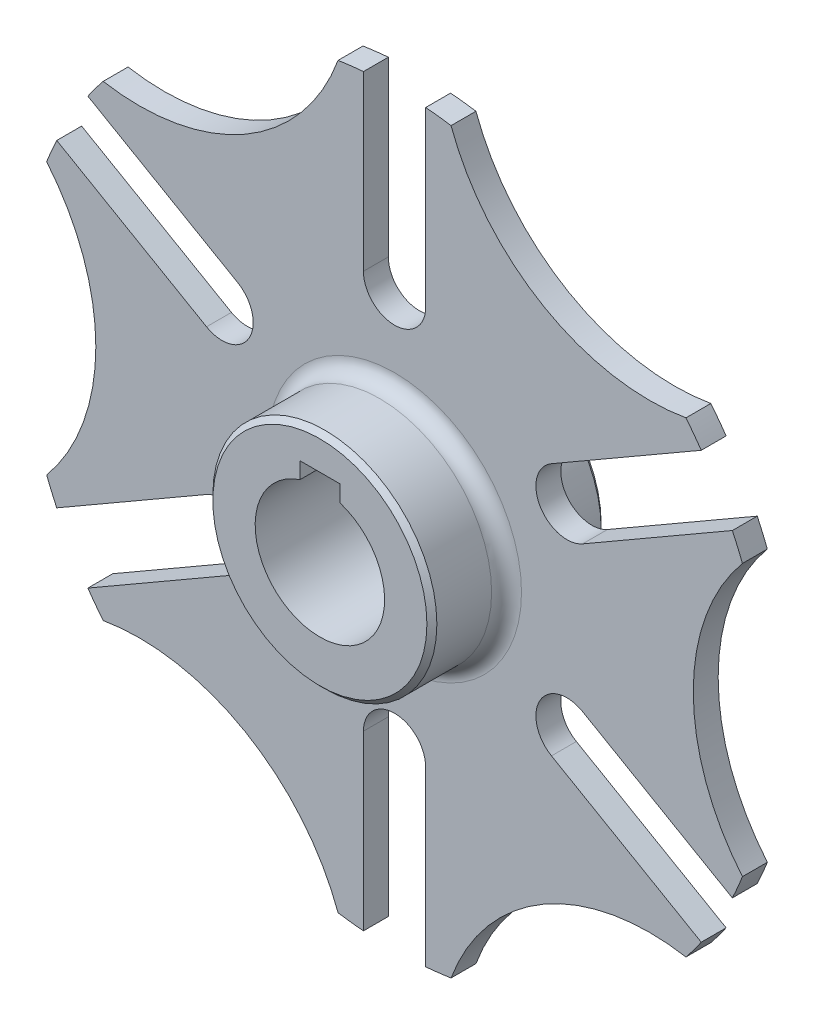
SolidWorks part; units mm, degrees
ref_plane "Front Plane" through (0, 0, 0) normal (0, 0, 1) x (1, 0, 0)
ref_plane "Top Plane" through (0, 0, 0) normal (0, 1, 0) x (1, 0, 0)
ref_plane "Right Plane" through (0, 0, 0) normal (1, 0, 0) x (0, 0, -1)
sketch "Sketch1" plane through (0, 0, 0) normal (0, 0, 1) x (1, 0, 0)
  circle A0 centre (0, 0) radius 75
  dimension "D1" = 150
extrude "Boss-Extrude1" add sketch "Sketch1" along normal mid plane 5 contours A0
sketch "Sketch2" plane through (0, 0, 0) normal (0, 0, 1) x (1, 0, 0)
  circle A0 centre (0, 0) radius 22.5
  dimension "D1" = 45
extrude "Boss-Extrude2" add sketch "Sketch2" along normal mid plane 35
sketch "Sketch3" plane through (0, 0, 17.5) normal (0, 0, 1) x (1, 0, 0)
  circle A0 centre (0, 0) radius 13
  dimension "D1" = 26
extrude "Cut-Extrude1" cut sketch "Sketch3" against normal blind 35
sketch "Sketch4" plane through (0, 0, 2.5) normal (0, 0, 1) x (1, 0, 0)
  line L0 (0, -90.256) -> (0, 75) construction
  line L1 (-102.8846, 0) -> (106.9882, 0) construction
  line L2 (0, 0) -> (62.7614, 108.7059) construction
  line L3 (0, 0) -> (51.25, 88.7676) construction
  line L4 (0, 40) -> (0, 75) construction
  line L5 (-6.25, 40) -> (-6.25, 74.7391)
  line L6 (6.25, 40) -> (6.25, 74.7391)
  line L7 (31.516, 25.4127) -> (61.601, 42.7822)
  line L8 (37.766, 14.5873) -> (67.851, 31.9569)
  line L9 (37.766, -14.5873) -> (67.851, -31.9569)
  line L10 (31.516, -25.4127) -> (61.601, -42.7822)
  line L11 (6.25, -40) -> (6.25, -74.7391)
  line L12 (-6.25, -40) -> (-6.25, -74.7391)
  line L13 (-31.516, -25.4127) -> (-61.601, -42.7822)
  line L14 (-37.766, -14.5873) -> (-67.851, -31.9569)
  line L15 (-37.766, 14.5873) -> (-67.851, 31.9569)
  line L16 (-31.516, 25.4127) -> (-61.601, 42.7822)
  circle A0 centre (0, 0) radius 102.5 construction
  arc A1 (11.3478, 74.1365) -> (58.5302, 46.8958) centre (51.25, 88.7676) ccw
  arc A2 (69.878, 27.2407) -> (69.878, -27.2407) centre (102.5, 0) ccw
  arc A3 (58.5302, -46.8958) -> (11.3478, -74.1365) centre (51.25, -88.7676) ccw
  arc A4 (-11.3478, -74.1365) -> (-58.5302, -46.8958) centre (-51.25, -88.7676) ccw
  arc A5 (-69.878, -27.2407) -> (-69.878, 27.2407) centre (-102.5, 0) ccw
  arc A6 (-58.5302, 46.8958) -> (-11.3478, 74.1365) centre (-51.25, 88.7676) ccw
  circle A7 centre (0, 0) radius 75 construction
  arc A8 (58.5302, 46.8958) -> (11.3478, 74.1365) centre (0, 0) ccw
  arc A9 (69.878, -27.2407) -> (69.878, 27.2407) centre (0, 0) ccw
  arc A10 (11.3478, -74.1365) -> (58.5302, -46.8958) centre (0, 0) ccw
  arc A11 (-58.5302, -46.8958) -> (-11.3478, -74.1365) centre (0, 0) ccw
  arc A12 (-69.878, 27.2407) -> (-69.878, -27.2407) centre (0, 0) ccw
  arc A13 (-11.3478, 74.1365) -> (-58.5302, 46.8958) centre (0, 0) ccw
  circle A14 centre (0, 0) radius 40 construction
  arc A15 (-6.25, 40) -> (6.25, 40) centre (0, 40) ccw
  arc A17 (-11.3478, 74.1365) -> (-58.5302, 46.8958) centre (0, 0) ccw
  arc A18 (6.25, 74.7391) -> (-6.25, 74.7391) centre (0, 0) ccw
  arc A19 (58.5302, 46.8958) -> (11.3478, 74.1365) centre (0, 0) ccw
  arc A20 (69.878, -27.2407) -> (69.878, 27.2407) centre (0, 0) ccw
  arc A21 (11.3478, -74.1365) -> (58.5302, -46.8958) centre (0, 0) ccw
  arc A22 (-58.5302, -46.8958) -> (-11.3478, -74.1365) centre (0, 0) ccw
  arc A23 (-69.878, 27.2407) -> (-69.878, -27.2407) centre (0, 0) ccw
  arc A24 (67.851, 31.9569) -> (61.601, 42.7822) centre (0, 0) ccw
  arc A25 (31.516, 25.4127) -> (37.766, 14.5873) centre (34.641, 20) ccw
  arc A26 (61.601, -42.7822) -> (67.851, -31.9569) centre (0, 0) ccw
  arc A27 (37.766, -14.5873) -> (31.516, -25.4127) centre (34.641, -20) ccw
  arc A28 (-6.25, -74.7391) -> (6.25, -74.7391) centre (0, 0) ccw
  arc A29 (6.25, -40) -> (-6.25, -40) centre (0, -40) ccw
  arc A30 (-67.851, -31.9569) -> (-61.601, -42.7822) centre (0, 0) ccw
  arc A31 (-31.516, -25.4127) -> (-37.766, -14.5873) centre (-34.641, -20) ccw
  arc A32 (-61.601, 42.7822) -> (-67.851, 31.9569) centre (0, 0) ccw
  arc A33 (-37.766, 14.5873) -> (-31.516, 25.4127) centre (-34.641, 20) ccw
  point P29 (0, 0)
  point P31 (0, 64.3838)
  point P63 (0, 0)
  circle M27 centre (0, 0) radius 75
  dimension "D2" = 205
  dimension "D3" = 42.5
  dimension "D4" = 6
  dimension "D5" = 80
  dimension "D1" = 30
  dimension "D6" = 12.5
  dimension "D7" = 6
extrude "Cut-Extrude2" cut sketch "Sketch4" against normal blind 35 contours A1 M27 | L7 A25 L8 M27 | A2 M27 | L9 A27 L10 M27 | A3 M27 | L11 A29 L12 M27 | A4 M27 | L13 A31 L14 M27 | A5 M27 | L15 A33 L16 M27 | A6 M27 | L5 A15 L6 M27
sketch "Sketch5" plane through (0, 0, 17.5) normal (0, 0, 1) x (1, 0, 0)
  line L0 (-4, 12.3693) -> (-4, 15.6693)
  line L3 (-4, 15.6693) -> (4, 15.6693)
  line L6 (-4, 15.6693) -> (-3.2155, 12.5961) construction
  line L8 (3.3163, 12.5699) -> (4, 15.6693) construction
  line L9 (4, 12.3693) -> (4, 15.6693)
  circle A0 centre (0, 0) radius 13 construction
  arc A1 (4, 12.3693) -> (-4, 12.3693) centre (0, 0) ccw
  point P0 (0, 0)
  dimension "D1" = 8
  dimension "D2" = 3.3
extrude "Cut-Extrude3" cut sketch "Sketch5" against normal blind 35
chamfer "Chamfer1" distance 1 angle 45 1 edges at (22.5, 0, 17.5)
fillet "Fillet1" radius 3 2 edges at (22.5, 0, -2.5) (22.5, 0, 2.5)
chamfer "Chamfer2" distance 1 angle 45 1 edges at (22.5, 0, -17.5)
